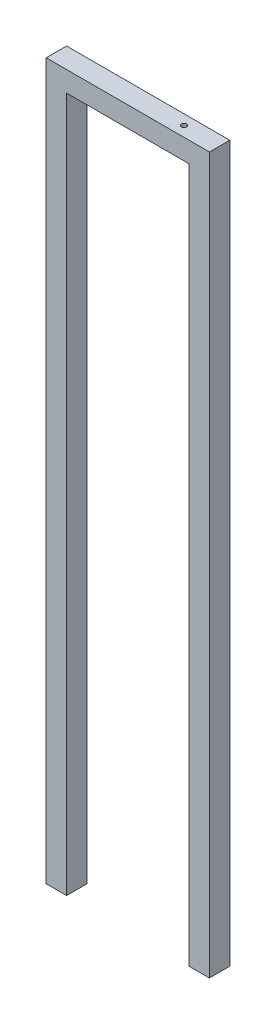
SolidWorks part; units mm, degrees
ref_plane "Front Plane" through (0, 0, 0) normal (0, 0, 1) x (1, 0, 0)
ref_plane "Top Plane" through (0, 0, 0) normal (0, 1, 0) x (1, 0, 0)
ref_plane "Right Plane" through (0, 0, 0) normal (1, 0, 0) x (0, 0, -1)
sketch "Sketch1" plane through (0, 0, 0) normal (0, 0, 1) x (1, 0, 0)
  line L0 (-76.5468, -608.9199) -> (-76.5468, 92.4101)
  line L1 (-76.5468, 92.4101) -> (83.4532, 92.4101)
  line L2 (83.4532, 92.4101) -> (83.4532, -608.9199)
  line L3 (-76.5468, -608.9199) -> (-56.5468, -608.9199)
  line L4 (-56.5468, -608.9199) -> (-56.5468, 72.4101)
  line L5 (-56.5468, 72.4101) -> (63.4532, 72.4101)
  line L6 (63.4532, 72.4101) -> (63.4532, -608.9199)
  line L7 (63.4532, -608.9199) -> (83.4532, -608.9199)
  line L8 (-56.5468, 72.4101) -> (-76.5468, 72.4101)
  line L9 (63.4532, 72.4101) -> (83.4532, 72.4101)
  dimension "D1" = 701.33
  dimension "D2" = 120
  dimension "D3" = 20
  dimension "D4" = 20
  dimension "D5" = 20
  dimension "D6" = 701.33
extrude "Boss-Extrude1" add sketch "Sketch1" along normal blind 20 contours L4 L8 L0 L3 | L9 L6 L7 L2 | L5 L9 L2 L1 L0 L8
sketch "Sketch2" plane through (0, 92.4101, 0) normal (0, 1, 0) x (1, 0, 0)
  line L0 (-76.5468, 0) -> (83.4532, 0) construction
  line L1 (83.4532, -20) -> (83.4532, 0) construction
  circle A0 centre (48.4532, -10) radius 2.5
  dimension "D1" = 5
  dimension "D2" = 10
  dimension "D3" = 35
extrude "Cut-Extrude1" cut sketch "Sketch2" against normal blind 10
